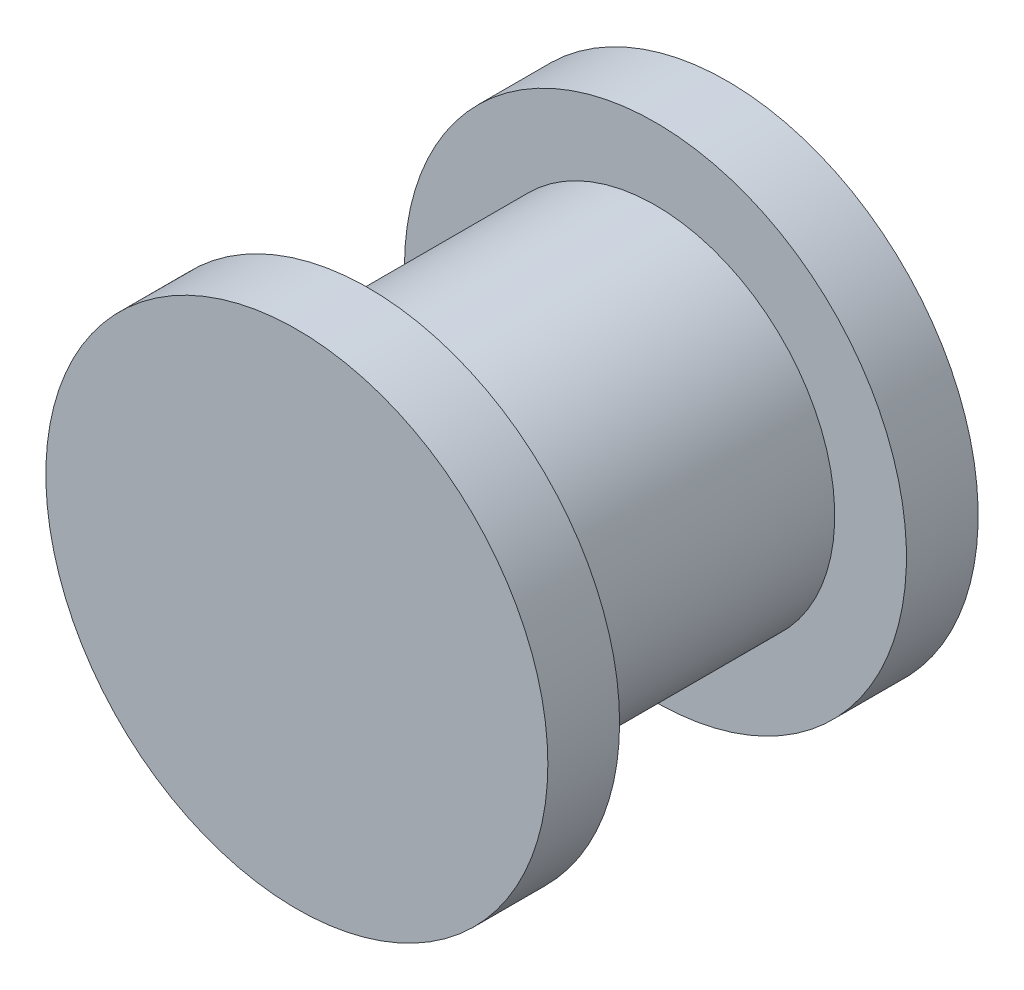
SolidWorks part; units mm, degrees
ref_plane "Front Plane" through (0, 0, 0) normal (0, 0, 1) x (1, 0, 0)
ref_plane "Top Plane" through (0, 0, 0) normal (0, 1, 0) x (1, 0, 0)
ref_plane "Right Plane" through (0, 0, 0) normal (1, 0, 0) x (0, 0, -1)
sketch "Sketch1" plane through (0, 0, 0) normal (0, 0, 1) x (1, 0, 0)
  circle A0 centre (0, 0) radius 12.5
  dimension "D1" = 25
extrude "Boss-Extrude1" add sketch "Sketch1" along normal blind 20
sketch "Sketch2" plane through (0, 0, 20) normal (0, 0, 1) x (1, 0, 0)
  circle A0 centre (0, 0) radius 17.5
  dimension "D1" = 35
extrude "Boss-Extrude2" add sketch "Sketch2" along normal blind 5
sketch "Sketch3" plane through (0, 0, 0) normal (0, 0, -1) x (-1, 0, 0)
  circle A0 centre (0, 0) radius 17.5
  dimension "D1" = 35
extrude "Boss-Extrude3" add sketch "Sketch3" along normal blind 5
